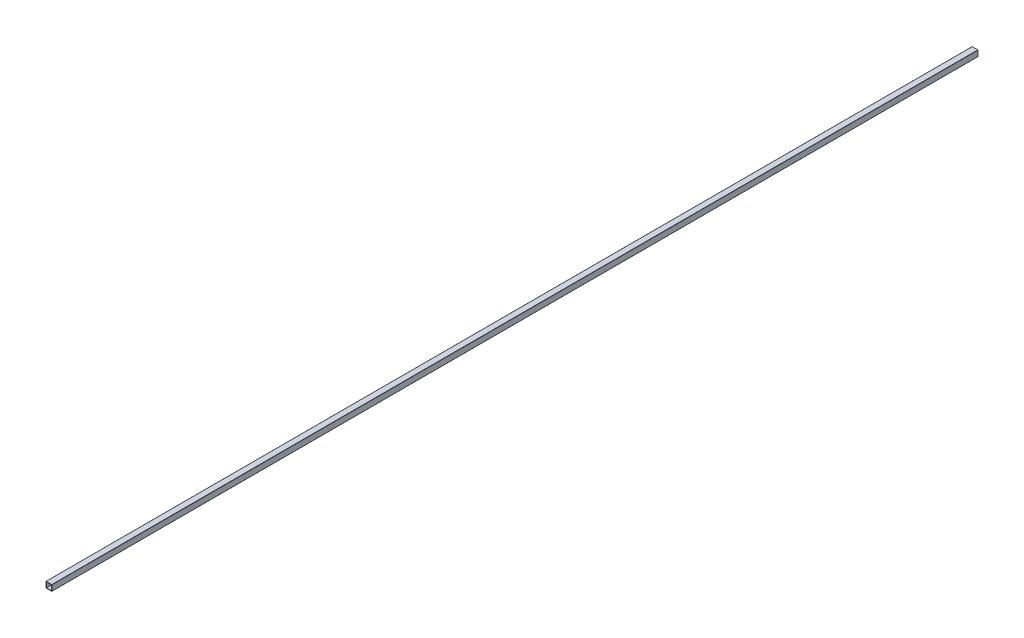
SolidWorks part; units mm, degrees
material "AISI 1035 Acero (SS)"
ref_plane "Alzado" through (0, 0, 0) normal (0, 0, 1) x (1, 0, 0)
ref_plane "Planta" through (0, 0, 0) normal (0, 1, 0) x (1, 0, 0)
ref_plane "Vista lateral" through (0, 0, 0) normal (1, 0, 0) x (0, 0, -1)
sketch "Croquis1" plane through (0, 0, 0) normal (0, 0, 1) x (1, 0, 0)
  line L0 (-16.39, -16.39) -> (-16.39, 16.39)
  line L1 (-18.05, -19.05) -> (18.05, -19.05)
  line L2 (-19.05, -18.05) -> (-19.05, 18.05)
  line L3 (-18.05, 19.05) -> (18.05, 19.05)
  line L4 (19.05, -18.05) -> (19.05, 18.05)
  line L5 (-19.05, -19.05) -> (19.05, 19.05) construction
  line L6 (-19.05, 19.05) -> (19.05, -19.05) construction
  line L7 (-16.39, 16.39) -> (16.39, 16.39)
  line L8 (16.39, -16.39) -> (16.39, 16.39)
  line L9 (-16.39, -16.39) -> (16.39, -16.39)
  line L10 (-19.05, 19.05) -> (19.05, 19.05) construction
  line L11 (19.05, -19.05) -> (19.05, 19.05) construction
  line L12 (-19.05, -19.05) -> (19.05, -19.05) construction
  line L13 (-19.05, -19.05) -> (-19.05, 19.05) construction
  arc A0 (18.05, 19.05) -> (19.05, 18.05) centre (18.05, 18.05) cw
  arc A1 (18.05, -19.05) -> (19.05, -18.05) centre (18.05, -18.05) ccw
  arc A2 (-18.05, -19.05) -> (-19.05, -18.05) centre (-18.05, -18.05) cw
  arc A3 (-19.05, 18.05) -> (-18.05, 19.05) centre (-18.05, 18.05) cw
  point P0 (0, 0)
  dimension "D2" = 1
  dimension "D1" = 38.1
  dimension "D3" = 2.66
extrude "Saliente-Extruir1" add sketch "Croquis1" along normal blind 6000
